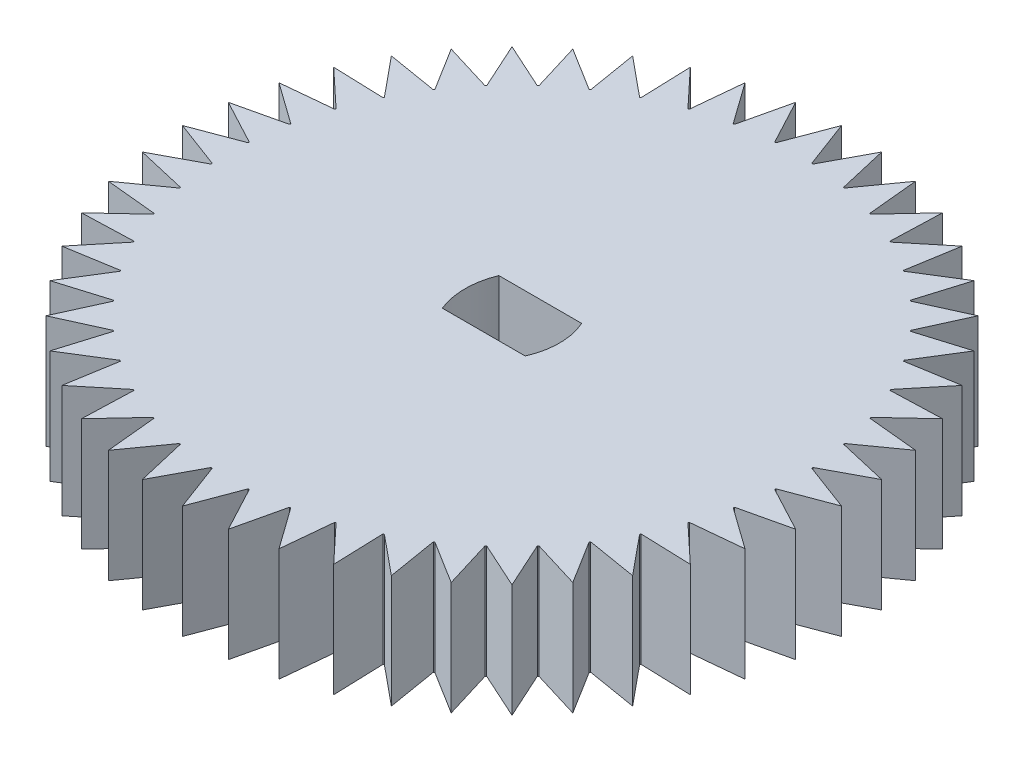
SolidWorks part; units mm, degrees
ref_plane "Спереди" through (0, 0, 0) normal (0, 0, 1) x (1, 0, 0)
ref_plane "Сверху" through (0, 0, 0) normal (0, 1, 0) x (1, 0, 0)
ref_plane "Справа" through (0, 0, 0) normal (1, 0, 0) x (0, 0, -1)
sketch "Эскиз1" plane through (0, 0, 0) normal (0, 1, 0) x (1, 0, 0)
  line L0 (2.2842, 17.3503) -> (2.8954, 14.7179)
  line L1 (1.0126, 14.9658) -> (2.2842, 17.3503)
  line L2 (4.5293, 16.9037) -> (4.7917, 14.2141)
  line L3 (2.9573, 14.7056) -> (4.5293, 16.9037)
  line L4 (0, 1.5) -> (2.2, 1.5)
  line L5 (0, 1.5) -> (-2.2, 1.5)
  line L6 (0, -1.5) -> (-2.2, -1.5)
  line L7 (0, -1.5) -> (2.2, -1.5)
  line L299 (6.697, 16.1679) -> (6.606, 13.467)
  line L303 (4.8515, 14.1938) -> (6.697, 16.1679)
  line L304 (0, 17.5) -> (0.9495, 14.9699)
  line L305 (-0.9495, 14.9699) -> (0, 17.5)
  line L306 (8.75, 15.1554) -> (8.3073, 12.4896)
  line L307 (6.6626, 13.4391) -> (8.75, 15.1554)
  line L308 (10.6533, 13.8837) -> (9.8664, 11.2984)
  line L309 (8.3598, 12.4545) -> (10.6533, 13.8837)
  line L310 (12.3744, 12.3744) -> (11.2567, 9.9139)
  line L311 (9.9139, 11.2567) -> (12.3744, 12.3744)
  line L312 (13.8837, 10.6533) -> (12.4545, 8.3598)
  line L313 (11.2984, 9.8664) -> (13.8837, 10.6533)
  line L314 (15.1554, 8.75) -> (13.4391, 6.6626)
  line L315 (12.4896, 8.3073) -> (15.1554, 8.75)
  line L316 (16.1679, 6.697) -> (14.1938, 4.8515)
  line L317 (13.467, 6.606) -> (16.1679, 6.697)
  line L318 (16.9037, 4.5293) -> (14.7056, 2.9573)
  line L319 (14.2141, 4.7917) -> (16.9037, 4.5293)
  line L320 (17.3503, 2.2842) -> (14.9658, 1.0126)
  line L321 (14.7179, 2.8954) -> (17.3503, 2.2842)
  line L322 (17.5, 0) -> (14.9699, -0.9495)
  line L323 (14.9699, 0.9495) -> (17.5, 0)
  line L324 (17.3503, -2.2842) -> (14.7179, -2.8954)
  line L325 (14.9658, -1.0126) -> (17.3503, -2.2842)
  line L326 (16.9037, -4.5293) -> (14.2141, -4.7917)
  line L327 (14.7056, -2.9573) -> (16.9037, -4.5293)
  line L328 (16.1679, -6.697) -> (13.467, -6.606)
  line L329 (14.1938, -4.8515) -> (16.1679, -6.697)
  line L330 (15.1554, -8.75) -> (12.4896, -8.3073)
  line L331 (13.4391, -6.6626) -> (15.1554, -8.75)
  line L332 (13.8837, -10.6533) -> (11.2984, -9.8664)
  line L333 (12.4545, -8.3598) -> (13.8837, -10.6533)
  line L334 (12.3744, -12.3744) -> (9.9139, -11.2567)
  line L335 (11.2567, -9.9139) -> (12.3744, -12.3744)
  line L336 (10.6533, -13.8837) -> (8.3598, -12.4545)
  line L337 (9.8664, -11.2984) -> (10.6533, -13.8837)
  line L338 (8.75, -15.1554) -> (6.6626, -13.4391)
  line L339 (8.3073, -12.4896) -> (8.75, -15.1554)
  line L340 (6.697, -16.1679) -> (4.8515, -14.1938)
  line L341 (6.606, -13.467) -> (6.697, -16.1679)
  line L342 (4.5293, -16.9037) -> (2.9573, -14.7056)
  line L343 (4.7917, -14.2141) -> (4.5293, -16.9037)
  line L344 (2.2842, -17.3503) -> (1.0126, -14.9658)
  line L345 (2.8954, -14.7179) -> (2.2842, -17.3503)
  line L346 (0, -17.5) -> (-0.9495, -14.9699)
  line L347 (0.9495, -14.9699) -> (0, -17.5)
  line L348 (-2.2842, -17.3503) -> (-2.8954, -14.7179)
  line L349 (-1.0126, -14.9658) -> (-2.2842, -17.3503)
  line L350 (-4.5293, -16.9037) -> (-4.7917, -14.2141)
  line L351 (-2.9573, -14.7056) -> (-4.5293, -16.9037)
  line L352 (-6.697, -16.1679) -> (-6.606, -13.467)
  line L353 (-4.8515, -14.1938) -> (-6.697, -16.1679)
  line L354 (-8.75, -15.1554) -> (-8.3073, -12.4896)
  line L355 (-6.6626, -13.4391) -> (-8.75, -15.1554)
  line L356 (-10.6533, -13.8837) -> (-9.8664, -11.2984)
  line L357 (-8.3598, -12.4545) -> (-10.6533, -13.8837)
  line L358 (-12.3744, -12.3744) -> (-11.2567, -9.9139)
  line L359 (-9.9139, -11.2567) -> (-12.3744, -12.3744)
  line L360 (-13.8837, -10.6533) -> (-12.4545, -8.3598)
  line L361 (-11.2984, -9.8664) -> (-13.8837, -10.6533)
  line L362 (-15.1554, -8.75) -> (-13.4391, -6.6626)
  line L363 (-12.4896, -8.3073) -> (-15.1554, -8.75)
  line L364 (-16.1679, -6.697) -> (-14.1938, -4.8515)
  line L365 (-13.467, -6.606) -> (-16.1679, -6.697)
  line L366 (-16.9037, -4.5293) -> (-14.7056, -2.9573)
  line L367 (-14.2141, -4.7917) -> (-16.9037, -4.5293)
  line L368 (-17.3503, -2.2842) -> (-14.9658, -1.0126)
  line L369 (-14.7179, -2.8954) -> (-17.3503, -2.2842)
  line L370 (-17.5, 0) -> (-14.9699, 0.9495)
  line L371 (-14.9699, -0.9495) -> (-17.5, 0)
  line L372 (-17.3503, 2.2842) -> (-14.7179, 2.8954)
  line L373 (-14.9658, 1.0126) -> (-17.3503, 2.2842)
  line L374 (-16.9037, 4.5293) -> (-14.2141, 4.7917)
  line L375 (-14.7056, 2.9573) -> (-16.9037, 4.5293)
  line L376 (-16.1679, 6.697) -> (-13.467, 6.606)
  line L377 (-14.1938, 4.8515) -> (-16.1679, 6.697)
  line L378 (-15.1554, 8.75) -> (-12.4896, 8.3073)
  line L379 (-13.4391, 6.6626) -> (-15.1554, 8.75)
  line L380 (-13.8837, 10.6533) -> (-11.2984, 9.8664)
  line L381 (-12.4545, 8.3598) -> (-13.8837, 10.6533)
  line L382 (-12.3744, 12.3744) -> (-9.9139, 11.2567)
  line L383 (-11.2567, 9.9139) -> (-12.3744, 12.3744)
  line L384 (-10.6533, 13.8837) -> (-8.3598, 12.4545)
  line L385 (-9.8664, 11.2984) -> (-10.6533, 13.8837)
  line L386 (-8.75, 15.1554) -> (-6.6626, 13.4391)
  line L387 (-8.3073, 12.4896) -> (-8.75, 15.1554)
  line L388 (-6.697, 16.1679) -> (-4.8515, 14.1938)
  line L389 (-6.606, 13.467) -> (-6.697, 16.1679)
  line L390 (-4.5293, 16.9037) -> (-2.9573, 14.7056)
  line L391 (-4.7917, 14.2141) -> (-4.5293, 16.9037)
  line L392 (-2.2842, 17.3503) -> (-1.0126, 14.9658)
  line L393 (-2.8954, 14.7179) -> (-2.2842, 17.3503)
  arc A0 (-2.2, 1.5) -> (-2.2, -1.5) centre (1.4803, 0) ccw
  arc A1 (2.2, 1.5) -> (2.2, -1.5) centre (-1.1791, 0) cw
  circle A3 centre (0, 0) radius 15
  point P158 (0, 0)
  point P224 (0, 0)
extrude "Бобышка-Вытянуть5" add sketch "Эскиз1" along normal blind 6 contours A3 | A3 L344 L345 | A3 L342 L343 | A3 L340 L341 | A3 L338 L339 | A3 L336 L337 | A3 L334 L335 | A3 L346 L347 | A3 L348 L349 | A3 L350 L351 | A3 L352 L353 | A3 L354 L355 | A3 L356 L357 | A3 L358 L359 | A3 L360 L361 | A3 L362 L363 | A3 L364 L365 | A3 L366 L367 | A3 L368 L369 | A3 L370 L371 | A3 L372 L373 | A3 L374 L375 | A3 L376 L377 | A3 L378 L379 | A3 L380 L381 | A3 L382 L383 | A3 L384 L385 | A3 L386 L387 | A3 L388 L389 | A3 L390 L391 | A3 L392 L393 | A3 L304 L305 | A3 L0 L1 | A3 L2 L3 | A3 L299 L303 | A3 L306 L307 | A3 L308 L309 | A3 L310 L311 | A3 L312 L313 | A3 L314 L315 | A3 L316 L317 | A3 L318 L319 | A3 L320 L321 | A3 L322 L323 | A3 L324 L325 | A3 L326 L327 | A3 L328 L329 | A3 L330 L331 | A3 L332 L333
